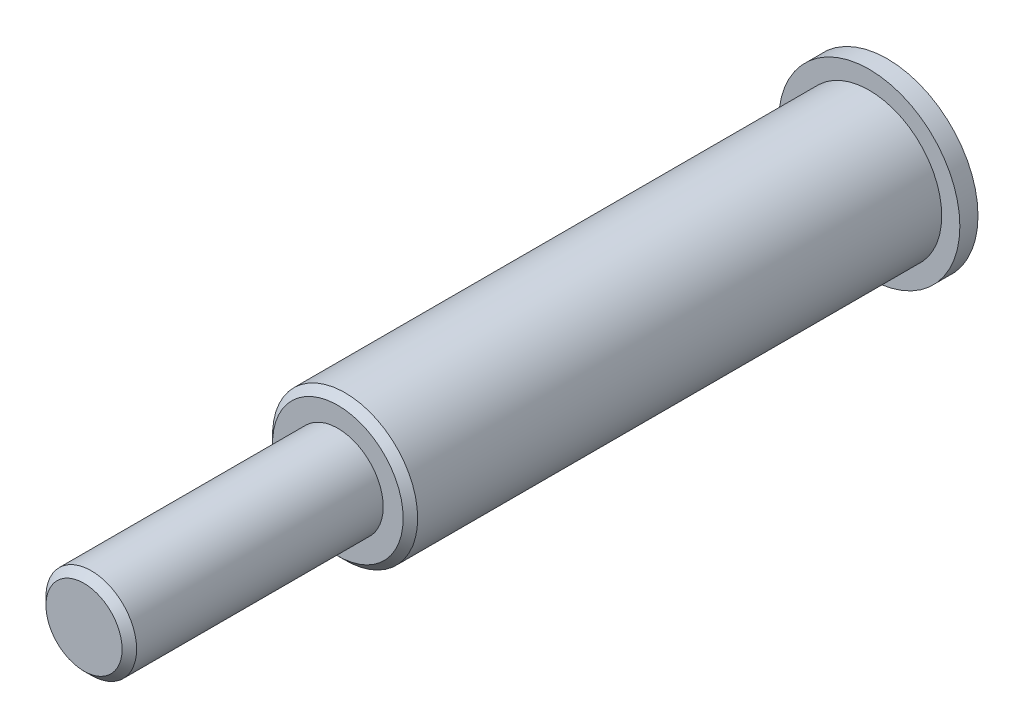
SolidWorks part; units mm, degrees
ref_plane "Front Plane" through (0, 0, 0) normal (0, 0, 1) x (1, 0, 0)
ref_plane "Top Plane" through (0, 0, 0) normal (0, 1, 0) x (1, 0, 0)
ref_plane "Right Plane" through (0, 0, 0) normal (1, 0, 0) x (0, 0, -1)
sketch "Sketch1" plane through (0, 0, 0) normal (0, 0, 1) x (1, 0, 0)
  circle A0 centre (0, 0) radius 4
  dimension "D1" = 8
extrude "Boss-Extrude1" add sketch "Sketch1" along normal blind 29.3
sketch "Sketch5" plane through (0, 0, 29.3) normal (0, 0, 1) x (1, 0, 0)
  circle A0 centre (0, 0) radius 2.5
  dimension "D1" = 5
extrude "Boss-Extrude4" add sketch "Sketch5" along normal blind 14
sketch "Sketch6" plane through (0, 0, 0) normal (0, 0, -1) x (-1, 0, 0)
  circle A0 centre (0, 0) radius 5
  dimension "D1" = 10
extrude "Boss-Extrude5" add sketch "Sketch6" along normal blind 1
chamfer "Chamfer1" distance 0.4 angle 45 2 edges at (4, 0, 29.3) (2.5, 0, 43.3)
